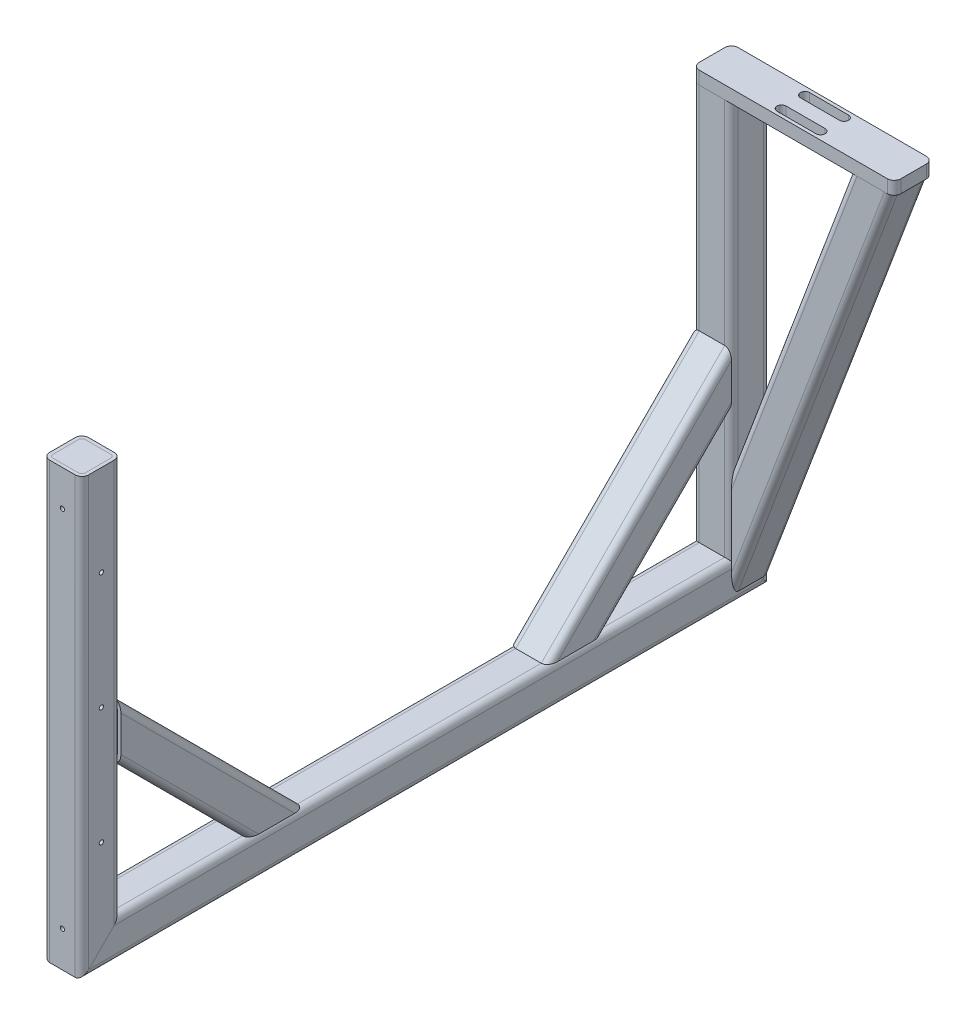
SolidWorks part; units mm, degrees
material "Q235"
ref_plane "前视" through (0, 0, 0) normal (0, 0, 1) x (1, 0, 0)
ref_plane "上视" through (0, 0, 0) normal (0, 1, 0) x (1, 0, 0)
ref_plane "右视" through (0, 0, 0) normal (1, 0, 0) x (0, 0, -1)
sketch3d "3D草图1"
  line L0 (0, 0, 0) -> (0, -320, 0)
  line L1 (0, -320, 0) -> (0, -320, 500)
  line L2 (0, -320, 500) -> (0, 0, 500)
  line L3 (0, -170, 0) -> (0, -320, 150)
  line L4 (0, -170, 500) -> (0, -320, 350)
  line L6 (0, 0, 0) -> (60, 0, 0) construction
  line L7 (0, -170, 0) -> (0, -170, 500) construction
  dimension "D1" = 150
  dimension "D2" = 320
  dimension "D3" = 500
  dimension "D4" = 45
  dimension "D8" = 60
other "结构构件1"
ref_plane "基准面1" through (0, 0, 0) normal (0, -1, 0) x (1, 0, 0)
sketch "Sketch1" plane through (0, 0, 0) normal (0, -1, 0) x (1, 0, 0)
  line L0 (-9.8, -12.4) -> (9.8, -12.4)
  line L1 (-12.4, -9.8) -> (-12.4, 9.8)
  line L2 (9.8, 12.4) -> (-9.8, 12.4)
  line L3 (12.4, 9.8) -> (12.4, -9.8)
  line L4 (-9.8, -15) -> (9.8, -15)
  line L5 (-15, -9.8) -> (-15, 9.8)
  line L6 (9.8, 15) -> (-9.8, 15)
  line L7 (15, 9.8) -> (15, -9.8)
  arc A0 (15, 9.8) -> (9.8, 15) centre (9.8, 9.8) ccw
  arc A1 (9.8, -15) -> (15, -9.8) centre (9.8, -9.8) ccw
  arc A2 (-15, -9.8) -> (-9.8, -15) centre (-9.8, -9.8) ccw
  arc A3 (-9.8, 15) -> (-15, 9.8) centre (-9.8, 9.8) ccw
  arc A4 (-9.8, 12.4) -> (-12.4, 9.8) centre (-9.8, 9.8) ccw
  arc A5 (12.4, 9.8) -> (9.8, 12.4) centre (9.8, 9.8) ccw
  arc A6 (9.8, -12.4) -> (12.4, -9.8) centre (9.8, -9.8) ccw
  arc A7 (-12.4, -9.8) -> (-9.8, -12.4) centre (-9.8, -9.8) ccw
  point P0 (-15, 0)
  point P1 (15, 0)
  point P2 (0, 15)
  point P3 (0, -15)
  point P4 (0, 0)
  point P5 (-15, -15)
  point P6 (15, -15)
  point P7 (15, 15)
  point P8 (-15, 15)
  point P33 (0, 0)
  dimension "D1" = 5.2
  dimension "Thickness" = 2.6
  dimension "V_leg" = 30
other "结构构件2"
ref_plane "基准面2" through (0, -170, 500) normal (0, -0.7071, -0.7071) x (1, 0, 0)
sketch "Sketch11" plane through (0, -170, 500) normal (0, -0.7071, -0.7071) x (1, 0, 0)
  line L0 (-9.8, -12.4) -> (9.8, -12.4)
  line L1 (-12.4, -9.8) -> (-12.4, 9.8)
  line L2 (9.8, 12.4) -> (-9.8, 12.4)
  line L3 (12.4, 9.8) -> (12.4, -9.8)
  line L4 (-9.8, -15) -> (9.8, -15)
  line L5 (-15, -9.8) -> (-15, 9.8)
  line L6 (9.8, 15) -> (-9.8, 15)
  line L7 (15, 9.8) -> (15, -9.8)
  arc A0 (15, 9.8) -> (9.8, 15) centre (9.8, 9.8) ccw
  arc A1 (9.8, -15) -> (15, -9.8) centre (9.8, -9.8) ccw
  arc A2 (-15, -9.8) -> (-9.8, -15) centre (-9.8, -9.8) ccw
  arc A3 (-9.8, 15) -> (-15, 9.8) centre (-9.8, 9.8) ccw
  arc A4 (-9.8, 12.4) -> (-12.4, 9.8) centre (-9.8, 9.8) ccw
  arc A5 (12.4, 9.8) -> (9.8, 12.4) centre (9.8, 9.8) ccw
  arc A6 (9.8, -12.4) -> (12.4, -9.8) centre (9.8, -9.8) ccw
  arc A7 (-12.4, -9.8) -> (-9.8, -12.4) centre (-9.8, -9.8) ccw
  point P0 (-15, 0)
  point P1 (15, 0)
  point P2 (0, 15)
  point P3 (0, -15)
  point P4 (0, 0)
  point P5 (-15, -15)
  point P6 (15, -15)
  point P7 (15, 15)
  point P8 (-15, 15)
  point P33 (0, 0)
  dimension "D1" = 5.2
  dimension "Thickness" = 2.6
  dimension "V_leg" = 30
other "结构构件3"
ref_plane "基准面3" through (0, -170, 0) normal (0, -0.7071, 0.7071) x (1, 0, 0)
sketch "Sketch12" plane through (0, -170, 0) normal (0, -0.7071, 0.7071) x (1, 0, 0)
  line L0 (-9.8, -12.4) -> (9.8, -12.4)
  line L1 (-12.4, -9.8) -> (-12.4, 9.8)
  line L2 (9.8, 12.4) -> (-9.8, 12.4)
  line L3 (12.4, 9.8) -> (12.4, -9.8)
  line L4 (-9.8, -15) -> (9.8, -15)
  line L5 (-15, -9.8) -> (-15, 9.8)
  line L6 (9.8, 15) -> (-9.8, 15)
  line L7 (15, 9.8) -> (15, -9.8)
  arc A0 (15, 9.8) -> (9.8, 15) centre (9.8, 9.8) ccw
  arc A1 (9.8, -15) -> (15, -9.8) centre (9.8, -9.8) ccw
  arc A2 (-15, -9.8) -> (-9.8, -15) centre (-9.8, -9.8) ccw
  arc A3 (-9.8, 15) -> (-15, 9.8) centre (-9.8, 9.8) ccw
  arc A4 (-9.8, 12.4) -> (-12.4, 9.8) centre (-9.8, 9.8) ccw
  arc A5 (12.4, 9.8) -> (9.8, 12.4) centre (9.8, 9.8) ccw
  arc A6 (9.8, -12.4) -> (12.4, -9.8) centre (9.8, -9.8) ccw
  arc A7 (-12.4, -9.8) -> (-9.8, -12.4) centre (-9.8, -9.8) ccw
  point P0 (-15, 0)
  point P1 (15, 0)
  point P2 (0, 15)
  point P3 (0, -15)
  point P4 (0, 0)
  point P5 (-15, -15)
  point P6 (15, -15)
  point P7 (15, 15)
  point P8 (-15, 15)
  point P33 (0, 0)
  dimension "D1" = 5.2
  dimension "Thickness" = 2.6
  dimension "V_leg" = 30
sketch "草图5" plane through (0, 0, 0) normal (0, 1, 0) x (1, 0, 0)
  line L0 (0, 0) -> (60, 0) construction
  line L1 (135, -15) -> (-9.8, -15)
  line L2 (140.2, -9.8) -> (140.2, 9.8)
  line L3 (135, 15) -> (-9.8, 15)
  line L4 (-15, -9.8) -> (-15, 9.8)
  line L5 (140.2, -15) -> (-15, 15) construction
  line L6 (140.2, 15) -> (-15, -15) construction
  line L7 (-9.8, 15) -> (9.8, 15) construction
  line L8 (-15, -9.8) -> (-15, 9.8) construction
  arc A0 (-9.8, -15) -> (-15, -9.8) centre (-9.8, -9.8) cw
  arc A1 (-9.8, 15) -> (-15, 9.8) centre (-9.8, 9.8) ccw
  arc A2 (-15, -9.8) -> (-9.8, -15) centre (-9.8, -9.8) ccw construction
  arc A3 (135, -15) -> (140.2, -9.8) centre (135, -9.8) ccw
  arc A4 (140.2, 9.8) -> (135, 15) centre (135, 9.8) ccw
  point P0 (62.6, 0)
  dimension "D1" = 150
extrude "凸台-拉伸1" add sketch "草图5" along normal blind 10 separate body
sketch "草图6" plane through (0, 0, 0) normal (0, 0, 1) x (1, 0, 0)
  line L0 (122.2, 0) -> (15, -285)
  line L1 (-9.8, 0) -> (135, 0) construction
  line L2 (140.2, 10) -> (140.2, 0) construction
  line L3 (15, -310.2) -> (15, 0) construction
  line L5 (9.8, -335) -> (-9.8, -335) construction
  dimension "D1" = 18
  dimension "D2" = 50
other "结构构件5"
ref_plane "基准面5" through (122.2, 0, 0) normal (-0.3521, -0.936, 0) x (0.936, -0.3521, 0)
sketch "Sketch14" plane through (122.2, 0, 0) normal (-0.3521, -0.936, 0) x (0.936, -0.3521, 0)
  line L0 (-9.8, -12.4) -> (9.8, -12.4)
  line L1 (-12.4, -9.8) -> (-12.4, 9.8)
  line L2 (9.8, 12.4) -> (-9.8, 12.4)
  line L3 (12.4, 9.8) -> (12.4, -9.8)
  line L4 (-9.8, -15) -> (9.8, -15)
  line L5 (-15, -9.8) -> (-15, 9.8)
  line L6 (9.8, 15) -> (-9.8, 15)
  line L7 (15, 9.8) -> (15, -9.8)
  arc A0 (15, 9.8) -> (9.8, 15) centre (9.8, 9.8) ccw
  arc A1 (9.8, -15) -> (15, -9.8) centre (9.8, -9.8) ccw
  arc A2 (-15, -9.8) -> (-9.8, -15) centre (-9.8, -9.8) ccw
  arc A3 (-9.8, 15) -> (-15, 9.8) centre (-9.8, 9.8) ccw
  arc A4 (-9.8, 12.4) -> (-12.4, 9.8) centre (-9.8, 9.8) ccw
  arc A5 (12.4, 9.8) -> (9.8, 12.4) centre (9.8, 9.8) ccw
  arc A6 (9.8, -12.4) -> (12.4, -9.8) centre (9.8, -9.8) ccw
  arc A7 (-12.4, -9.8) -> (-9.8, -12.4) centre (-9.8, -9.8) ccw
  point P0 (-15, 0)
  point P1 (15, 0)
  point P2 (0, 15)
  point P3 (0, -15)
  point P4 (0, 0)
  point P5 (-15, -15)
  point P6 (15, -15)
  point P7 (15, 15)
  point P8 (-15, 15)
  point P33 (0, 0)
  dimension "D1" = 5.2
  dimension "Thickness" = 2.6
  dimension "V_leg" = 30
other "剪裁/延伸1"
other "剪裁/延伸2"
other "剪裁/延伸3"
sketch "草图13" plane through (0, 10, 0) normal (0, 1, 0) x (1, 0, 0)
  line L0 (-15, 0) -> (62.6, 0) construction
  line L1 (-15, 9.8) -> (-15, -9.8) construction
  line L2 (0, 0) -> (60, 0) construction
  line L3 (62.6, 0) -> (62.6, 15) construction
  line L4 (135, 15) -> (-9.8, 15) construction
  line L5 (47.6, 9) -> (77.6, 9) construction
  line L6 (47.6, 12.5) -> (77.6, 12.5)
  line L7 (47.6, 5.5) -> (77.6, 5.5)
  line L9 (47.6, -9) -> (77.6, -9) construction
  line L10 (47.6, -12.5) -> (77.6, -12.5)
  line L11 (47.6, -5.5) -> (77.6, -5.5)
  arc A0 (47.6, 12.5) -> (47.6, 5.5) centre (47.6, 9) ccw
  arc A1 (77.6, 5.5) -> (77.6, 12.5) centre (77.6, 9) ccw
  arc A2 (47.6, -12.5) -> (47.6, -5.5) centre (47.6, -9) cw
  arc A3 (77.6, -5.5) -> (77.6, -12.5) centre (77.6, -9) cw
  point P12 (62.6, 9)
  point P21 (62.6, -9)
  dimension "D1" = 30
  dimension "D2" = 7
  dimension "D3" = 18
extrude "切除-拉伸1" cut sketch "草图13" against normal up to next (10 mm away)
sketch "草图10" plane through (0, 0, 0) normal (0, 1, 0) x (1, 0, 0)
  line L0 (9.8, -487.6) -> (-9.8, -487.6) construction
  line L1 (12.4, -509.8) -> (12.4, -490.2) construction
  line L2 (-9.8, -512.4) -> (9.8, -512.4) construction
  line L3 (-12.4, -490.2) -> (-12.4, -509.8) construction
  line L4 (9.8, -487.6) -> (-9.8, -487.6)
  line L5 (12.4, -509.8) -> (12.4, -490.2)
  line L6 (-9.8, -512.4) -> (9.8, -512.4)
  line L7 (-12.4, -490.2) -> (-12.4, -509.8)
  arc A0 (12.4, -490.2) -> (9.8, -487.6) centre (9.8, -490.2) ccw construction
  arc A1 (9.8, -512.4) -> (12.4, -509.8) centre (9.8, -509.8) ccw construction
  arc A2 (-12.4, -509.8) -> (-9.8, -512.4) centre (-9.8, -509.8) ccw construction
  arc A3 (-9.8, -487.6) -> (-12.4, -490.2) centre (-9.8, -490.2) ccw construction
  arc A4 (12.4, -490.2) -> (9.8, -487.6) centre (9.8, -490.2) ccw
  arc A5 (9.8, -512.4) -> (12.4, -509.8) centre (9.8, -509.8) ccw
  arc A6 (-12.4, -509.8) -> (-9.8, -512.4) centre (-9.8, -509.8) ccw
  arc A7 (-9.8, -487.6) -> (-12.4, -490.2) centre (-9.8, -490.2) ccw
extrude "凸台-拉伸2" add sketch "草图10" against normal blind 2 separate body
hole_wizard "M4 螺纹孔1" positions "草图12" profile "草图11" tap size "M4" standard "Gb" end condition up to next
sketch "草图12" plane through (0, 0, 515) normal (0, 0, 1) x (1, 0, 0)
  line L0 (0, 0) -> (0, -320) construction
  line L1 (0, 0) -> (0, -167.5) construction
  line L2 (0, -167.5) -> (9.8, -167.5) construction
  line L3 (9.8, 0) -> (9.8, -335) construction
  point P0 (0, -27.5)
  point P15 (0, -307.5)
  dimension "D1" = 280
sketch "草图11" plane through (0, -27.5, 515) normal (1, 0, 0) x (0, -1, 0)
  line L0 (0, 0) -> (0, 2.6)
  line L1 (0, 2.6) -> (1.65, 2.6)
  line L2 (1.65, 2.6) -> (1.65, 0)
  line L5 (1.65, 0) -> (0, 0)
  line L11 (0, -6.35) -> (0, 107.95) construction
  dimension "通孔螺纹孔钻头直径" = 3.3
  dimension "通孔螺纹孔钻头深度" = 2.6
cosmetic thread "孔螺蚊线1" parameters "D2"=4
cosmetic thread "孔螺蚊线2" parameters "D2"=4
hole_wizard "M4 螺纹孔2" positions "草图15" profile "草图14" tap size "M4" standard "Gb"
sketch "草图15" plane through (15, 0, 0) normal (1, 0, 0) x (0, 0, -1)
  line L0 (-500, -320) -> (-500, 0) construction
  line L1 (-500, 0) -> (-500, -335) construction
  line L2 (-500, -160) -> (-425.2674, -160) construction
  line L3 (-515, -335) -> (15, -335) construction
  point P0 (-500, -70)
  point P4 (-500, -160)
  point P18 (-500, -250)
  dimension "D1" = 180
sketch "草图14" plane through (15, -70, 500) normal (0, 1, 0) x (0, 0, -1)
  line L0 (0, 0) -> (0, 11.0914)
  line L1 (0, 11.0914) -> (1.65, 10.1)
  line L2 (1.65, 10.1) -> (1.65, 0)
  line L5 (1.65, 0) -> (0, 0)
  line L10 (0, 11.0914) -> (-1.65, 10.1) construction
  line L11 (0, -6.35) -> (0, 107.95) construction
  dimension "螺纹孔钻头直径" = 3.3
  dimension "螺纹孔钻头深度" = 10.1
  dimension "导头角度" = 118
cosmetic thread "孔螺蚊线3" parameters "D1"=2.6, "D2"=4
cosmetic thread "孔螺蚊线4" parameters "D1"=2.6, "D2"=4
cosmetic thread "孔螺蚊线5" parameters "D1"=2.6, "D2"=4
